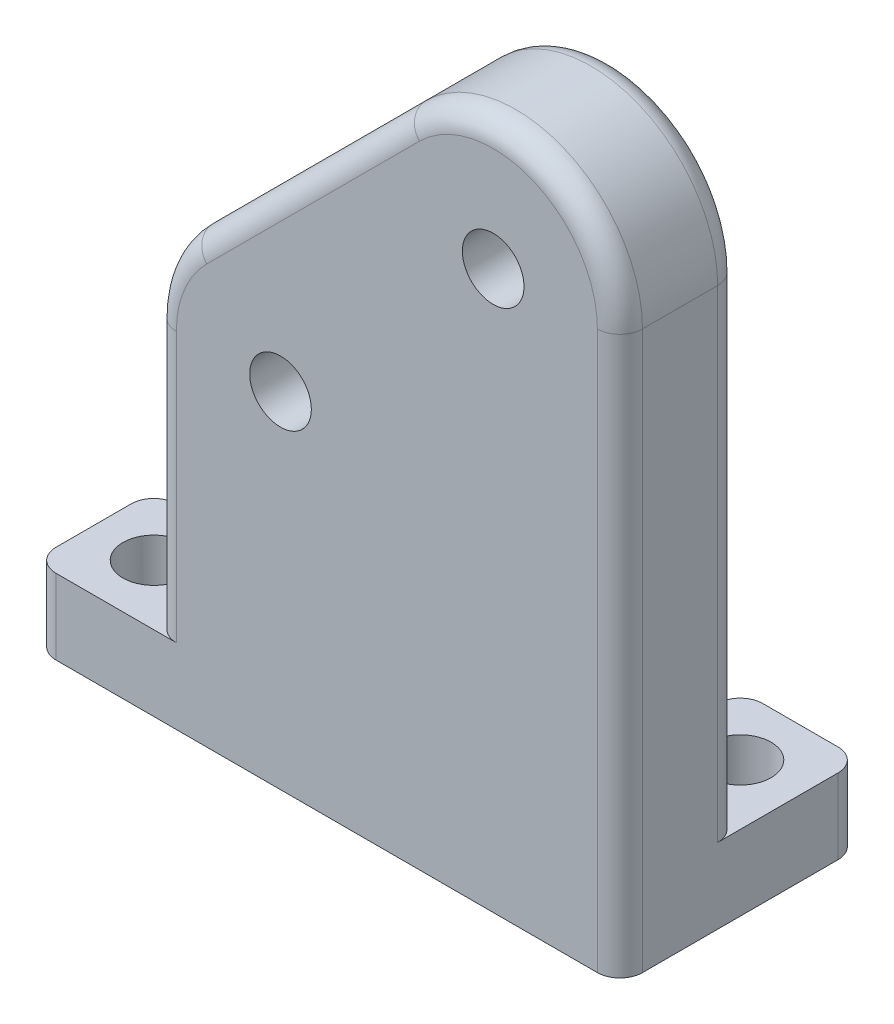
SolidWorks part; units mm, degrees
ref_plane "Plan de face" through (0, 0, 0) normal (0, 0, 1) x (1, 0, 0)
ref_plane "Plan de dessus" through (0, 0, 0) normal (0, 1, 0) x (1, 0, 0)
ref_plane "Plan de droite" through (0, 0, 0) normal (1, 0, 0) x (0, 0, -1)
sketch "Esquisse7" plane through (0, 0, 0) normal (0, 0, 1) x (1, 0, 0)
  line L0 (0, 0) -> (39, 0)
  line L2 (0, 0) -> (0, 5)
  line L3 (0, 5) -> (8, 5)
  line L6 (0, 0) -> (117.5195, 0) construction
  line L8 (8, 5) -> (8, 43.0312) construction
  line L9 (8, 43.0312) -> (24.6109, 43.0312) construction
  line L10 (8, 30) -> (39, 30) construction
  line L11 (8, 5) -> (8, 0) construction
  line L12 (23.5, 30) -> (23.5, 0) construction
  line L13 (23.5, 30) -> (5.8533, 12.3533) construction
  line L14 (23.5, 30) -> (6.9688, 46.5312) construction
  line L15 (39, 0) -> (39, 37.0711)
  line L17 (8, 5) -> (8, 22.9289)
  line L18 (10.4688, 28.8891) -> (24.6109, 43.0312)
  line L19 (-0.6421, 45.5) -> (47.255, 45.5) construction
  circle A0 centre (16.4289, 22.9289) radius 2.05
  circle A1 centre (30.5711, 37.0711) radius 2.05
  circle A2 centre (30.5711, 37.0711) radius 8.4289 construction
  arc A3 (24.6109, 43.0312) -> (39, 37.0711) centre (30.5711, 37.0711) cw
  circle A4 centre (16.4289, 22.9289) radius 8.4289 construction
  arc A5 (10.4688, 28.8891) -> (8, 22.9289) centre (16.4289, 22.9289) ccw
  point P21 (10, 5.3401)
  point P26 (9.6599, 5)
  dimension "D1" = 5
  dimension "D3" = 31
  dimension "D7" = 4.1
  dimension "D4" = 16.8579
  dimension "D2" = 8
  dimension "D5" = 45
  dimension "D6" = 30
  dimension "D8" = 45
  dimension "D9" = 45
  dimension "D10" = 10
extrude "Boss.-Extru.1" add sketch "Esquisse7" along normal blind 8
sketch "Esquisse11" plane through (0, 0, 0) normal (0, 0, -1) x (-1, 0, 0)
  line L0 (-39, 5) -> (-31, 5)
  line L1 (-31, 5) -> (-31, 0)
  line L6 (0, 0) -> (0, 5)
  line L7 (0, 5) -> (-8, 5)
  line L8 (-8, 5) -> (-8, 22.9289)
  line L9 (-10.4688, 28.8891) -> (-24.6109, 43.0312)
  line L10 (-39, 37.0711) -> (-39, 0)
  line L11 (-39, 0) -> (0, 0)
  line L12 (0, 0) -> (0, 5)
  line L13 (0, 5) -> (-8, 5)
  line L14 (-8, 5) -> (-8, 22.9289)
  line L15 (-10.4688, 28.8891) -> (-24.6109, 43.0312)
  line L16 (-39, 37.0711) -> (-39, 0)
  line L17 (-39, 0) -> (0, 0)
  arc A4 (-8, 22.9289) -> (-10.4688, 28.8891) centre (-16.4289, 22.9289) ccw
  arc A5 (-24.6109, 43.0312) -> (-39, 37.0711) centre (-30.5711, 37.0711) ccw
  arc A7 (-8, 22.9289) -> (-10.4688, 28.8891) centre (-16.4289, 22.9289) ccw
  arc A8 (-24.6109, 43.0312) -> (-39, 37.0711) centre (-30.5711, 37.0711) ccw
  line M19 (-39, 37.0711) -> (-39, 0)
  line M20 (-39, 0) -> (0, 0)
  dimension "D2" = 5
  dimension "D3" = 8
  dimension "D1" = 0
extrude "Boss.-Extru.4" add sketch "Esquisse11" along normal blind 8 contours L1 L0 M19 M20
sketch "Esquisse12" plane through (0, 5, 0) normal (0, 1, 0) x (1, 0, 0)
  line L0 (0, -4) -> (8, -4) construction
  line L1 (31, 4) -> (39, 4) construction
  line L2 (35, 8) -> (35, 0) construction
  line L3 (4, 0) -> (4, -8) construction
  line L4 (31, 0) -> (39, 0)
  line L5 (39, 0) -> (39, 8)
  line L6 (39, 8) -> (31, 8)
  line L7 (31, 8) -> (31, 0)
  line L8 (31, 0) -> (39, 0)
  line L9 (39, 0) -> (39, 8)
  line L10 (39, 8) -> (31, 8)
  line L11 (31, 8) -> (31, 0)
  line L12 (8, 0) -> (0, 0)
  line L13 (0, 0) -> (0, -8)
  line L14 (0, -8) -> (8, -8)
  line L15 (8, -8) -> (8, 0)
  line L16 (8, 0) -> (0, 0)
  line L17 (0, 0) -> (0, -8)
  line L18 (0, -8) -> (8, -8)
  line L24 (8, -8) -> (8, 0)
  circle A0 centre (4, -4) radius 2.05
  circle A1 centre (35, 4) radius 2.05
  dimension "D3" = 4.1
  dimension "D1" = 0
  dimension "D2" = 0
extrude "Enlèv. mat.-Extru.1" cut sketch "Esquisse12" against normal blind 10 contours A1 | A0
fillet "Congé1" radius 1.5 12 edges at (0, 2.5, 8) (0, 2.5, 0) (31, 2.5, -8) (39, 2.5, -8) (39, 21.0355, 0) (39, 18.5355, 8) (33.7967, 44.8584, 0) (33.7967, 44.8584, 8) (17.5398, 35.9602, 8) (17.5398, 35.9602, 0) (8, 13.9645, 0) (8, 13.9645, 8)
